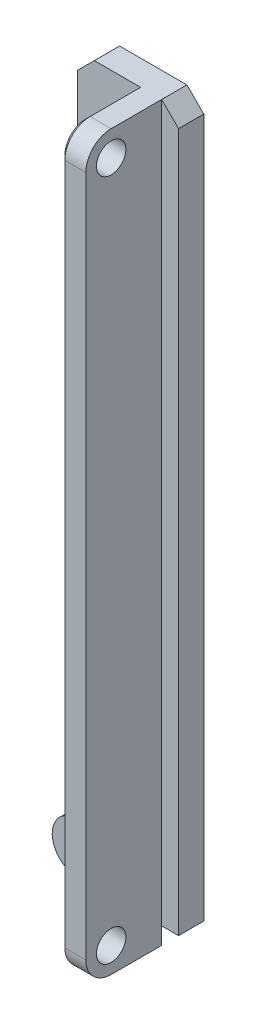
SolidWorks part; units mm, degrees
ref_plane "正面" through (0, 0, 0) normal (0, 0, 1) x (1, 0, 0)
ref_plane "平面" through (0, 0, 0) normal (0, 1, 0) x (1, 0, 0)
ref_plane "右側面" through (0, 0, 0) normal (1, 0, 0) x (0, 0, -1)
ref_plane "平面1" through (0, 0, -6) normal (0, 0, 1) x (1, 0, 0)
sketch "ｽｹｯﾁ1" plane through (0, 0, -6) normal (0, 0, 1) x (1, 0, 0)
  line L0 (5, 72) -> (-7, 72)
  line L1 (-7, 72) -> (-7, -7)
  line L2 (-7, -13) -> (5, -13)
  line L3 (5, -13) -> (5, 72)
  arc A0 (-7, -7) -> (-7, -13) centre (-7, -10) ccw
  dimension "D1" = 85
  dimension "D2" = 5
  dimension "D3" = 13
  dimension "D4" = 7
extrude "ﾎﾞｽ - 押し出し1" add sketch "ｽｹｯﾁ1" against normal blind 3
sketch "ｽｹｯﾁ2" plane through (-7, 0, 0) normal (-1, 0, 0) x (0, 0, 1)
  line L0 (-6, 72) -> (-6, 0)
  line L1 (-6, 0) -> (-9, 0)
  line L2 (-9, 0) -> (-9, 72)
  line L3 (-9, 72) -> (-6, 72)
extrude "ﾎﾞｽ - 押し出し2" add sketch "ｽｹｯﾁ2" along normal blind 1.5
sketch "ｽｹｯﾁ3" plane through (0, 0, -9) normal (0, 0, -1) x (-1, 0, 0)
  line L0 (3, -13) -> (3, 15)
  line L1 (3, 15) -> (4.5, 15)
  line L2 (4.5, 15) -> (4.5, 17)
  line L3 (4.5, 17) -> (0, 17)
  line L4 (0, 17) -> (0, -13)
  line L5 (0, -13) -> (3, -13)
extrude "ｶｯﾄ - 押し出し1" cut sketch "ｽｹｯﾁ3" against normal through all
sketch "ｽｹｯﾁ4" plane through (0, 0, -6) normal (0, 0, 1) x (1, 0, 0)
  line L0 (-8.5, 72) -> (-8.5, 3)
  line L1 (-8.5, 3) -> (-7, 3)
  line L2 (-7, 3) -> (-7, 72)
  line L3 (-7, 72) -> (-8.5, 72)
extrude "ｶｯﾄ - 押し出し2" cut sketch "ｽｹｯﾁ4" against normal through all
ref_plane "平面2" through (0, 0, 0) normal (-1, 0, 0) x (0, -1, 0)
sketch "ｽｹｯﾁ5" plane through (0, 0, 0) normal (-1, 0, 0) x (0, -1, 0)
  line L0 (-72, 3) -> (-72, -3)
  line L1 (-72, -3) -> (-72, -6)
  line L2 (-72, -6) -> (15, -6)
  line L3 (15, -6) -> (15, 3)
  line L4 (15, 3) -> (-72, 3)
  line L5 (55, -6) -> (-55, -6) construction
  line L6 (-72, -9) -> (-72, -6) construction
  point P6 (-92.5, -5)
  point P7 (-88.0095, -6)
  point P12 (-72, -6)
  dimension "D1" = 87
extrude "ﾎﾞｽ - 押し出し3" add sketch "ｽｹｯﾁ5" against normal blind 3
draft "抜き勾配1" type of draft neutral plane draft angle 45 faces to draft 1 face at (-7.75, 3, -7.5) neutral plane through (-7, 3, -9) neutral plane normal (-1, 0, 0) parameters "D1"=45
hole_wizard "Ø2.7 (2.7) 直径の穴1" positions "ｽｹｯﾁ7" profile "ｽｹｯﾁ6" hole size "Ø2.7" standard "Ansi Metric"
sketch "ｽｹｯﾁ7" plane through (0, 0, 0) normal (-1, 0, 0) x (0, 0, 1)
  line L0 (3, 72) -> (-6, 72) construction
  point P0 (0, 69)
  point P1 (0, -12)
  dimension "D1" = 3
  dimension "D2" = 81
sketch "ｽｹｯﾁ6" plane through (0, 69, 0) normal (0, 1, 0) x (0, 0, 1)
  line L0 (0, 0) -> (0, 5)
  line L1 (0, 5) -> (1.75, 5)
  line L2 (1.75, 5) -> (1.75, 0)
  line L5 (1.75, 0) -> (0, 0)
  line L11 (0, -6.35) -> (0, 107.95) construction
  dimension "通し穴の直径" = 3.5
  dimension "通し穴の深さ" = 5
fillet "ﾌｨﾚｯﾄ1" radius 3 2 edges at (1.5, 72, 3) (1.5, -15, 3)
chamfer "面取り1" distance 2 angle 45 1 edges at (-7, 72, -7.5)
chamfer "面取り2" distance 2 angle 45 1 edges at (5, 72, -7.5)
chamfer "面取り4" distance 0.5 angle 45 5 edges at (0, -15, -3) (0, -14.1213, 2.1213) (0, 28.5, 3) (0, 71.1213, 2.1213) (0, 72, -3)
